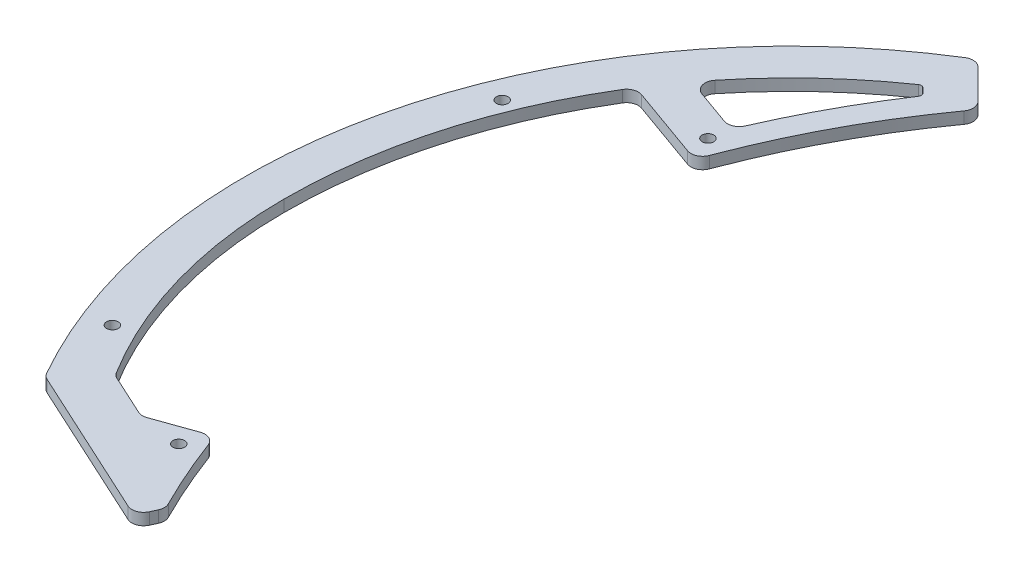
SolidWorks part; units mm, degrees
material "1060 Alloy"
ref_plane "Front Plane" through (0, 0, 0) normal (0, 0, 1) x (1, 0, 0)
ref_plane "Top Plane" through (0, 0, 0) normal (0, 1, 0) x (1, 0, 0)
ref_plane "Right Plane" through (0, 0, 0) normal (1, 0, 0) x (0, 0, -1)
sketch "Sketch1" plane through (0, 0, 0) normal (0, 1, 0) x (1, 0, 0)
  circle A0 centre (0, 0) radius 140
  dimension "D1" = 280
extrude "Boss-Extrude1" add sketch "Sketch1" along normal blind 3
sketch "Sketch19" plane through (0, 3, 0) normal (0, 1, 0) x (1, 0, 0)
  line L0 (-78.4889, 78.4889) -> (78.4889, -78.4889) construction
  line L1 (111, 45.9777) -> (45.9777, 111) construction
  line L2 (45.9777, 111) -> (-45.9777, 111) construction
  line L3 (-45.9777, 111) -> (-111, 45.9777) construction
  line L4 (-111, 45.9777) -> (-111, -45.9777) construction
  line L5 (-111, -45.9777) -> (-45.9777, -111) construction
  line L6 (-45.9777, -111) -> (45.9777, -111) construction
  line L7 (45.9777, -111) -> (111, -45.9777) construction
  line L8 (111, -45.9777) -> (111, 45.9777) construction
  line L9 (78.4889, 78.4889) -> (-78.4889, -78.4889) construction
  circle A0 centre (-89.0955, -67.8823) radius 1.5
  circle A1 centre (-89.0955, 67.8823) radius 1.5
  circle A2 centre (89.0955, 67.8823) radius 1.5
  circle A3 centre (89.0955, -67.8823) radius 1.5
  circle A4 centre (0, 0) radius 111 construction
  circle A5 centre (-67.8823, 89.0955) radius 1.5
  circle A6 centre (67.8823, 89.0955) radius 1.5
  circle A7 centre (67.8823, -89.0955) radius 1.5
  circle A8 centre (-67.8823, -89.0955) radius 1.5
  dimension "D5" = 3
  dimension "D1" = 15
  dimension "D6" = 111
extrude "Cut-Extrude3" cut sketch "Sketch19" against normal up to next
sketch "Sketch17" plane through (0, 0, 0) normal (0, -1, 0) x (1, 0, 0)
  line L0 (-50, 100) -> (-121.2436, 70)
  line L1 (-50, 100) -> (50, 100)
  line L2 (-121.2436, 70) -> (-121.2436, 140)
  line L3 (-121.2436, 140) -> (121.2436, 140)
  line L4 (121.2436, 140) -> (121.2436, 70)
  line L5 (121.2436, 70) -> (50, 100)
  circle A0 centre (0, 0) radius 140 construction
  dimension "D1" = 100
  dimension "D2" = 50
  dimension "D3" = 50
  dimension "D4" = 70
extrude "Cut-Extrude1" [suppressed] cut sketch "Sketch17" against normal up to next
sketch "Sketch25" plane through (0, 3, 0) normal (0, 1, 0) x (1, 0, 0)
  circle A0 centre (-124, 50) radius 1.5
  circle A1 centre (-124, -50) radius 1.5
  dimension "D1" = 3
  dimension "D2" = 50
  dimension "D3" = 50
  dimension "D4" = 124
extrude "Cut-Extrude10" cut sketch "Sketch25" against normal up to next
sketch "Sketch20" plane through (0, 3, 0) normal (0, 1, 0) x (1, 0, 0)
  line L0 (-72, 120.0666) -> (-50, 98.0666)
  line L1 (-50, 98.0666) -> (50, 98.0666)
  line L2 (50, 98.0666) -> (72, 120.0666)
  circle A1 centre (0, 0) radius 140 construction
  dimension "D1" = 144
  dimension "D2" = 100
  dimension "D3" = 50
extrude "Cut-Extrude4" cut sketch "Sketch20" against normal up to next
fillet "Fillet2" radius 10 2 edges at (50, 1.5, -98.0666) (-50, 1.5, -98.0666)
sketch "Sketch26" plane through (0, 3, 0) normal (0, 1, 0) x (1, 0, 0)
  line L0 (-121.2436, -70) -> (-79.057, -89.4493)
  line L1 (-79.057, -89.4493) -> (-76.4598, -83.816)
  line L2 (-100.1421, -66.5145) -> (-86.1288, -61.5152)
  line L3 (-86.1288, -61.5152) -> (-93.657, -40.4132) construction
  line L4 (-109.6127, 69.8932) -> (-86.1288, 61.5152)
  line L5 (-60.85, 108.9167) -> (-72, 120.0666)
  line L6 (-72, 120.0666) -> (-52.9289, 100.9956) construction
  line L7 (-86.1288, 61.5152) -> (-98.4946, 26.8531) construction
  line L8 (-112.4256, -60.8515) -> (-100.1421, -66.5145)
  line L9 (-130, 74.1477) -> (-130, -50) construction
  line L10 (-103.6984, 78.4005) -> (-88.1706, 72.861)
  line L11 (-73.3831, 107.3076) -> (-70.9931, 104.9176)
  circle A0 centre (-67.8823, 89.0955) radius 5 construction
  circle A1 centre (-89.0955, 67.8823) radius 5 construction
  circle A2 centre (-124, 50) radius 5 construction
  circle A3 centre (-89.0955, -67.8823) radius 5 construction
  circle A4 centre (-67.8823, -89.0955) radius 5 construction
  circle A5 centre (-124, -50) radius 5 construction
  arc A6 (-112.4256, -60.8515) -> (-130, 0) centre (-15.8636, 0) cw
  arc A7 (-72, 120.0666) -> (72, 120.0666) centre (0, 0) ccw construction
  arc A8 (-86.1288, -61.5152) -> (-76.4598, -83.816) centre (86.3028, 0) ccw
  arc A9 (-86.1288, 61.5152) -> (-60.85, 108.9167) centre (86.3028, 0) cw
  arc A10 (-130, 0) -> (-109.6127, 69.8932) centre (0, 0) cw
  arc A11 (-73.3831, 107.3076) -> (-103.6984, 78.4005) centre (0, 0) ccw
  arc A12 (-88.1706, 72.861) -> (-70.9931, 104.9176) centre (86.3028, 0) cw
  arc A13 (-72, 120.0666) -> (-121.2436, -70) centre (0, 0) ccw
  circle M1 centre (-89.0955, -67.8823) radius 1.5
  circle M2 centre (-89.0955, 67.8823) radius 1.5
  circle M3 centre (89.0955, 67.8823) radius 1.5
  circle M4 centre (89.0955, -67.8823) radius 1.5
  circle M5 centre (-67.8823, 89.0955) radius 1.5
  circle M6 centre (67.8823, 89.0955) radius 1.5
  circle M7 centre (67.8823, -89.0955) radius 1.5
  circle M8 centre (-67.8823, -89.0955) radius 1.5
  circle M9 centre (-124, 50) radius 1.5
  circle M10 centre (-124, -50) radius 1.5
  arc M11 (-72, 120.0666) -> (72, 120.0666) centre (0, 0) ccw
  line M12 (72, 120.0666) -> (52.9289, 100.9956)
  arc M13 (52.9289, 100.9956) -> (45.8579, 98.0666) centre (45.8579, 108.0666) cw
  line M14 (45.8579, 98.0666) -> (-45.8579, 98.0666)
  arc M15 (-45.8579, 98.0666) -> (-52.9289, 100.9956) centre (-45.8579, 108.0666) cw
  line M16 (-52.9289, 100.9956) -> (-72, 120.0666)
  dimension "D1" = 10
  dimension "D4" = 12
  dimension "D5" = 130
  dimension "D6" = 6
  dimension "D7" = 10
  dimension "D2" = 70
  dimension "D3" = 10
  dimension "D8" = 10
  dimension "D9" = 10
extrude "Cut-Extrude11" cut sketch "Sketch26" against normal up to next (3 mm away) contours A10 A6 L8 L2 A8 L1 L0 A9 L4 M11 M12 M13 M14 M15 M16 M4 M6 M8 M7 M5 M3 | L10 A12 L11 A11 | M5 | M2 | M9 | M1 | M10
sketch "Sketch23" [suppressed] plane through (0, 3, 0) normal (0, 1, 0) x (1, 0, 0)
  line L0 (-72.365, -73.9737) -> (-80.4987, -93.2894)
  line L1 (-72, 120.0666) -> (-52.9289, 100.9956) construction
  line L2 (-121.2436, -70) -> (-50, -100) construction
  arc A0 (-54.9334, 103) -> (-72.365, -73.9737) centre (114.6363, -3.0477) ccw
  arc A3 (-72.365, -73.9737) -> (-54.9334, -109.0955) centre (114.6363, -3.0477) ccw construction
  circle A4 centre (-67.8823, -89.0955) radius 1.5 construction
  dimension "D1" = 103
  dimension "D2" = 20
  dimension "D3" = 200
  dimension "D4" = 90
  dimension "D5" = 10
extrude "Cut-Extrude8" [suppressed] cut sketch "Sketch23" against normal through all and the other way through all
sketch "Sketch24" [suppressed] plane through (0, 3, 0) normal (0, 1, 0) x (1, 0, 0)
  line L0 (-87.2371, 61.6912) -> (-76.1181, 57.0584)
  line L1 (-108.2916, -62.4334) -> (-85.8817, -71.87)
  line L3 (-121.2436, -70) -> (-78.3054, -88.0808) construction
  line L4 (-88.8916, -62.3806) -> (-77.7417, -57.7349)
  line L5 (-120, 50) -> (0, 0) construction
  line L6 (0, 0) -> (-120, -50) construction
  line L7 (-76.1181, 57.0584) -> (-77.7417, -57.7349)
  arc A1 (-87.2371, 61.6912) -> (-67.7264, 105.0625) centre (114.6363, -3.0477) cw
  arc A2 (-54.9334, 103) -> (-72.365, -73.9737) centre (114.6363, -3.0477) ccw construction
  arc A3 (-67.7264, 105.0625) -> (-108.2916, -62.4334) centre (0, 0) ccw
  circle A4 centre (-120, 50) radius 5 construction
  circle A5 centre (-120, -50) radius 5 construction
  arc A6 (-85.8817, -71.87) -> (-88.8916, -62.3806) centre (114.6363, -3.0477) cw
  circle A8 centre (-89.0955, -67.8823) radius 1.5 construction
  circle A9 centre (-89.0955, 67.8823) radius 1.5 construction
  dimension "D2" = 10
  dimension "D3" = 5
  dimension "D4" = 12
  dimension "D5" = 12
  dimension "D1" = 5
  dimension "D6" = 12
extrude "Cut-Extrude9" [suppressed] cut sketch "Sketch24" against normal up to next
fillet "Fillet4" [suppressed] radius 5
fillet "Fillet5" [suppressed] radius 3
fillet "Fillet6" radius 3 12 edges at (-72, 1.5, -120.0666) (-88.1706, 1.5, -72.861) (-103.6984, 1.5, -78.4005) (-112.4256, 1.5, 60.8515) (-100.1421, 1.5, 66.5145) (-86.1288, 1.5, 61.5152) (-76.4598, 1.5, 83.816) (-79.057, 1.5, 89.4493) (-109.6127, 1.5, -69.8932) (-86.1288, 1.5, -61.5152) (-60.85, 1.5, -108.9167) (-121.2436, 1.5, 70)
fillet "Fillet7" radius 1 2 edges at (-73.3831, 1.5, -107.3076) (-70.9931, 1.5, -104.9176)
equation "\"D3@Sketch20\" = \"D2@Sketch20\" / 2"
